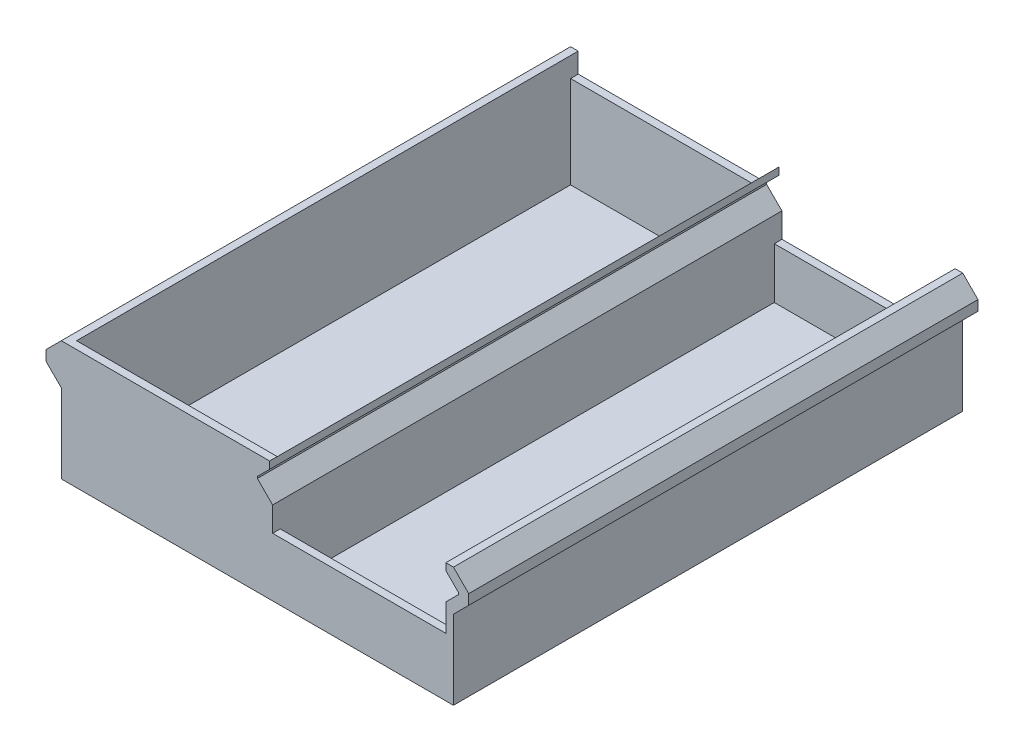
SolidWorks part; units mm, degrees
ref_plane "前视基准面" through (0, 0, 0) normal (0, 0, 1) x (1, 0, 0)
ref_plane "上视基准面" through (0, 0, 0) normal (0, 1, 0) x (1, 0, 0)
ref_plane "右视基准面" through (0, 0, 0) normal (1, 0, 0) x (0, 0, -1)
other "Configuration Table"
sketch "草图1" plane through (0, 0, 0) normal (0, 0, 1) x (1, 0, 0)
  line L0 (77, 0) -> (-77, 0)
  line L1 (-77, 0) -> (-77, 31)
  line L2 (-77, 31) -> (-83, 37)
  line L3 (-83, 37) -> (-83, 41)
  line L4 (-83, 41) -> (-77, 47)
  line L5 (-77, 47) -> (77, 47)
  line L6 (0, 47) -> (0, 0) construction
  line L7 (77, 0) -> (77, 31)
  line L8 (77, 31) -> (83, 37)
  line L9 (83, 37) -> (83, 41)
  line L10 (83, 41) -> (77, 47)
  dimension "D1" = 154
  dimension "D2" = 47
  dimension "D3" = 45
  dimension "D4" = 45
  dimension "D5" = 6
  dimension "D6" = 16
extrude "凸台-拉伸1" add sketch "草图1" against normal blind 200
sketch "草图2" plane through (0, 47, 0) normal (0, 1, 0) x (1, 0, 0)
  line L8 (-74, 3) -> (74, 3)
  line L9 (74, 3) -> (74, 197)
  line L10 (74, 197) -> (-74, 197)
  line L11 (-74, 197) -> (-74, 3)
  line L12 (-74, 3) -> (74, 3)
  line L13 (74, 3) -> (74, 197)
  line L14 (74, 197) -> (-74, 197)
  line L15 (-74, 197) -> (-74, 3)
  dimension "D1" = 3
extrude "切除-拉伸1" cut sketch "草图2" against normal offset from surface (44 mm away) 3 up to face at (0, 0, -100)
sketch "草图3" plane through (0, 3, 0) normal (0, 1, 0) x (1, 0, 0)
  line L0 (-74, 3) -> (74, 3) construction
  line L1 (0, 3) -> (0, 197)
  line L2 (74, 197) -> (-74, 197) construction
extrude "拉伸-薄壁1" add sketch "草图3" along normal up to surface (44 mm away) thin
sketch "草图5" plane through (0, 0, -200) normal (0, 0, -1) x (-1, 0, 0)
  line L0 (-74, 47) -> (-74, 44.3431)
  line L1 (-77, 47) -> (77, 47) construction
  line L2 (-74, 44.3431) -> (-79, 39.3431)
  line L3 (-79, 39.3431) -> (-79, 38.6569)
  line L4 (-79, 38.6569) -> (-74, 33.6569)
  line L5 (-74, 33.6569) -> (-74, 23)
  line L6 (-74, 23) -> (-6, 23)
  line L7 (-6, 23) -> (-6, 32.6569)
  line L8 (-6, 32.6569) -> (0, 38.6569)
  line L9 (0, 38.6569) -> (0, 39.3431)
  line L10 (0, 39.3431) -> (-4.794, 44.1372)
  line L11 (-4.794, 44.1372) -> (-4.794, 47)
  line L12 (-4.794, 47) -> (-74, 47)
  line L13 (-72.9645, 43.9645) -> (-78, 38.9289) construction
  line L14 (-74, 3) -> (-74, 47) construction
  line L15 (-78, 37.6569) -> (-73, 32.6569) construction
  line L17 (-78, 38.9289) -> (-78, 37.6569) construction
  line L18 (-73, 28) -> (-6, 28) construction
  line L19 (-6, 47) -> (-6, 3) construction
  line L20 (-1, 37.6569) -> (-1, 38.9289) construction
  line L21 (-1, 38.9289) -> (-6.0355, 43.9645) construction
  point P25 (-6, 23)
  point P28 (-4.1208, 44.8104)
  point P29 (0, 38.6569)
  dimension "D1" = 1
  dimension "D2" = 1
  dimension "D3" = 5
  dimension "D4" = 1
  dimension "D5" = 1
extrude "切除-拉伸2" cut sketch "草图5" against normal through all
sketch "草图6" plane through (0, 0, -3) normal (0, 0, -1) x (-1, 0, 0)
  line L0 (-4.8284, 47) -> (3, 47)
  line L1 (-4.794, 47) -> (77, 47) construction
  line L2 (3, 47) -> (3, 39.1716) construction
  line L3 (3, 47) -> (3, 3) construction
  line L4 (3, 39.1716) -> (-4.8284, 47)
  line L5 (0, 39.3431) -> (-4.794, 44.1372) construction
  line L6 (3, 39.1716) -> (74, 39.1716)
  line L7 (74, 3) -> (74, 47) construction
  line L8 (74, 39.1716) -> (74, 47)
  line L9 (74, 47) -> (3, 47)
  dimension "D1" = 2
extrude "切除-拉伸3" cut sketch "草图6" along normal through all
